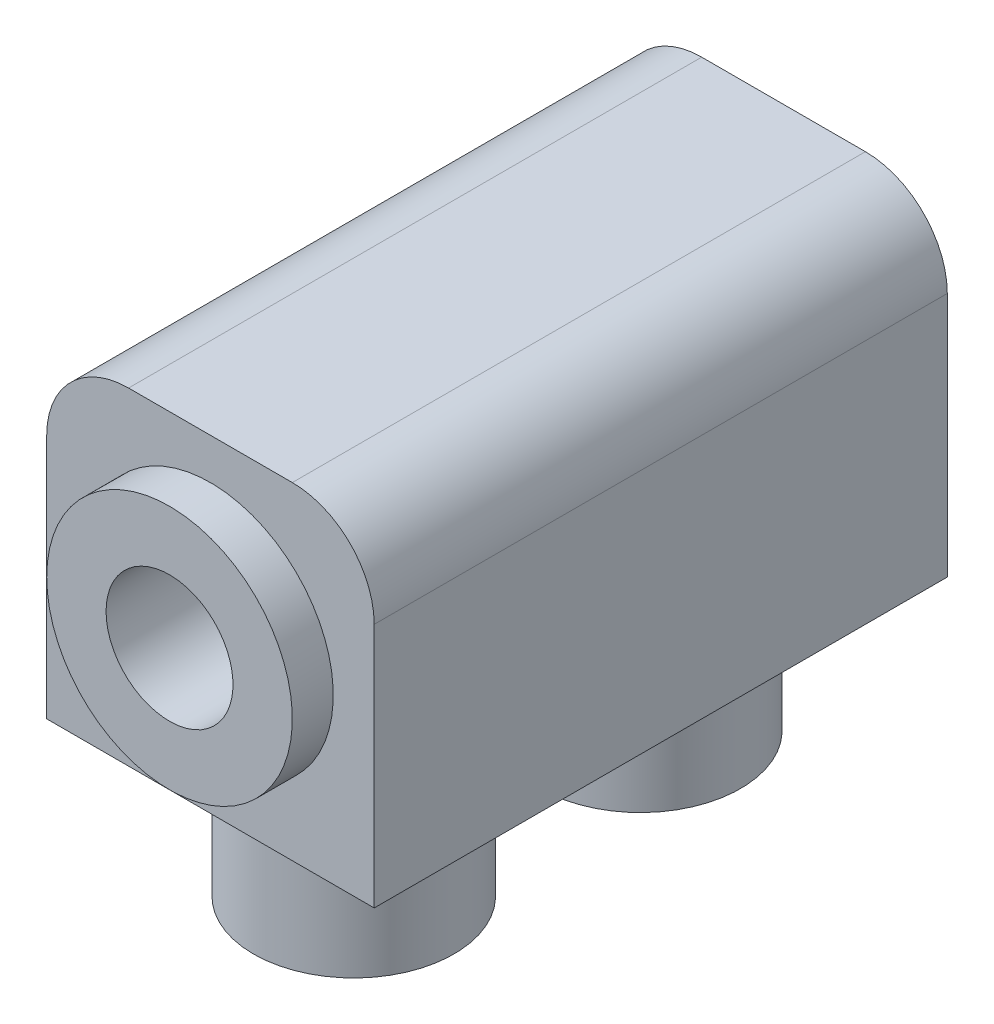
SolidWorks part; units mm, degrees
ref_plane "Front Plane" through (0, 0, 0) normal (0, 0, 1) x (1, 0, 0)
ref_plane "Top Plane" through (0, 0, 0) normal (0, 1, 0) x (1, 0, 0)
ref_plane "Right Plane" through (0, 0, 0) normal (1, 0, 0) x (0, 0, -1)
sketch "Sketch1" plane through (0, 0, 0) normal (0, 1, 0) x (1, 0, 0)
  line L1 (0, 0) -> (8, 0)
  line L2 (0, 0) -> (0, 14)
  line L3 (0, 14) -> (8, 14)
  line L4 (8, 0) -> (8, 14)
  dimension "D1" = 8
  dimension "D2" = 14
extrude "Boss-Extrude1" add sketch "Sketch1" along normal blind 8
sketch "Sketch2" plane through (0, 0, 0) normal (0, -1, 0) x (1, 0, 0)
  line L0 (0, -7) -> (8, -7) construction
  line L1 (0, -14) -> (0, 0) construction
  line L2 (8, 0) -> (8, -14) construction
  line L3 (4, -3.5) -> (4, -10.5) construction
  circle A0 centre (4, -10.5) radius 2.45
  circle A1 centre (4, -3.5) radius 2.45
  point P10 (4, -7)
  dimension "D1" = 4.9
  dimension "D2" = 7
extrude "Boss-Extrude2" add sketch "Sketch2" along normal blind 3.5
fillet "Fillet1" radius 2 2 edges at (8, 8, -7) (0, 8, -7)
sketch "Sketch5" plane through (0, 0, -14) normal (0, 0, -1) x (-1, 0, 0)
  line L0 (-4, 0) -> (-4, 4) construction
  line L1 (-6.45, 0) -> (-1.55, 0) construction
  line L2 (-4, 4) -> (-4, 8) construction
  line L3 (-6, 8) -> (-2, 8) construction
  circle A0 centre (-4, 4) radius 3
  dimension "D1" = 6
extrude "Boss-Extrude3" add sketch "Sketch5" along normal blind 1 contours A0
ref_plane "Plane1" through (0, 0, -7) normal (0, 0, -1) x (-1, 0, 0)
mirror "Mirror1" about plane through (0, 0, -7) normal (0, 0, -1) of "Boss-Extrude3"
sketch "Sketch6" plane through (0, 0, -15) normal (0, 0, -1) x (-1, 0, 0)
  circle A0 centre (-4, 4) radius 1.55
  dimension "D1" = 3.1
extrude "Cut-Extrude1" cut sketch "Sketch6" against normal through all
